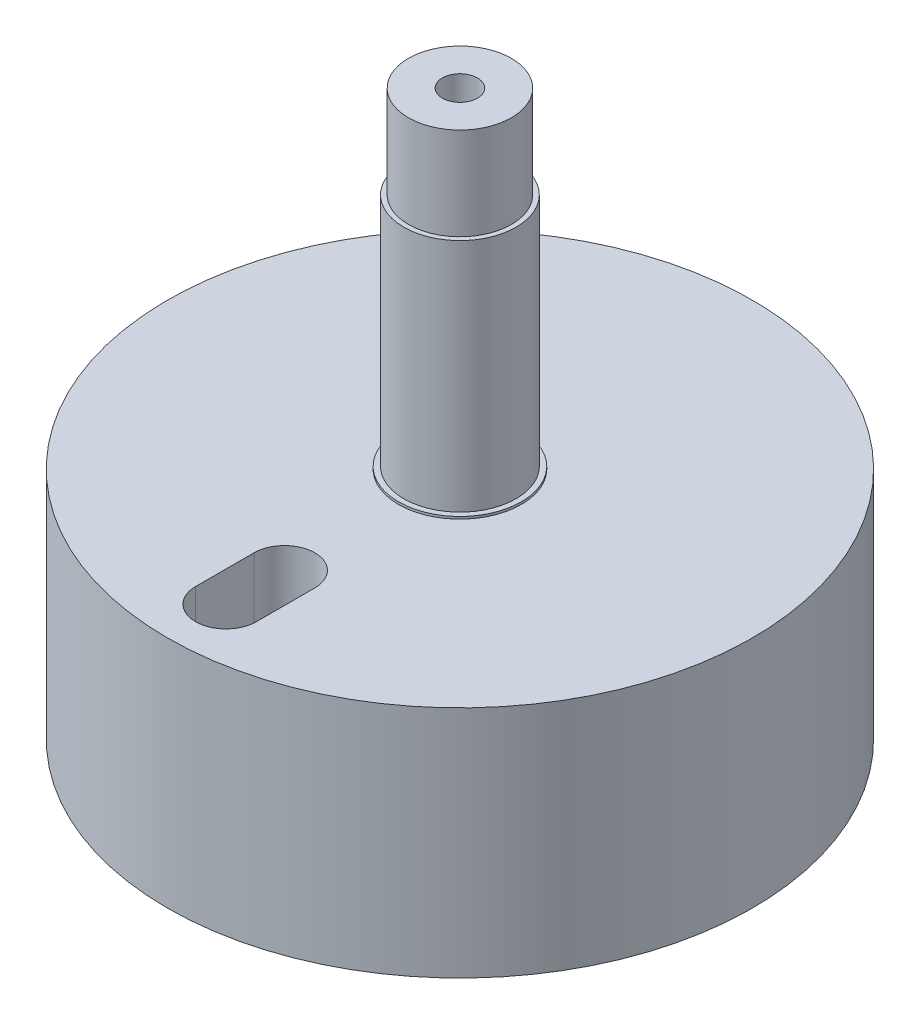
SolidWorks part; units mm, degrees
ref_plane "Front Plane" through (0, 0, 0) normal (0, 0, 1) x (1, 0, 0)
ref_plane "Top Plane" through (0, 0, 0) normal (0, 1, 0) x (1, 0, 0)
ref_plane "Right Plane" through (0, 0, 0) normal (1, 0, 0) x (0, 0, -1)
sketch "Sketch1" plane through (0, 0, 0) normal (0, 1, 0) x (1, 0, 0)
  circle A0 centre (0, 0) radius 25
  dimension "D1" = 50
extrude "Boss-Extrude1" add sketch "Sketch1" along normal blind 20
sketch "Sketch3" plane through (0, 20, 0) normal (0, 1, 0) x (1, 0, 0)
  line L0 (-2.6, -15) -> (-2.6, -20)
  line L1 (2.6, -15) -> (2.6, -20)
  line L2 (-2.6, -17.5) -> (2.6, -17.5) construction
  arc A0 (2.6, -15) -> (-2.6, -15) centre (0, -15) ccw
  arc A1 (-2.6, -20) -> (2.6, -20) centre (0, -20) ccw
  point P7 (0, -17.5)
  dimension "D1" = 5.2
  dimension "D2" = 5
  dimension "D3" = 15
extrude "Cut-Extrude2" cut sketch "Sketch3" against normal blind 10
sketch "Sketch5" plane through (0, 10, 0) normal (0, 1, 0) x (1, 0, 0)
  circle A0 centre (0, -17.5) radius 1.5
  dimension "D1" = 3
extrude "Cut-Extrude3" cut sketch "Sketch5" against normal through all
sketch "Sketch2" plane through (0, 20, 0) normal (0, 1, 0) x (1, 0, 0)
  circle A0 centre (0, 0) radius 25
  circle A1 centre (0, 0) radius 5.25
  dimension "D1" = 50
  dimension "D2" = 10.5
extrude "Boss-Extrude2" add sketch "Sketch2" along normal blind 0.2 contours A1
sketch "Sketch7" plane through (0, 20.2, 0) normal (0, 1, 0) x (1, 0, 0)
  circle A0 centre (0, 0) radius 4.8
  dimension "D1" = 9.6
extrude "Boss-Extrude3" add sketch "Sketch7" along normal blind 20.1
sketch "Sketch8" plane through (0, 40.3, 0) normal (0, 1, 0) x (1, 0, 0)
  circle A0 centre (0, 0) radius 4.4
  dimension "D1" = 8.8
extrude "Boss-Extrude4" add sketch "Sketch8" along normal blind 7.9
sketch "Sketch6" plane through (0, 0, 0) normal (0, -1, 0) x (1, 0, 0)
  circle A0 centre (0, 0) radius 1.5
  dimension "D1" = 3
extrude "Cut-Extrude4" cut sketch "Sketch6" against normal through all
